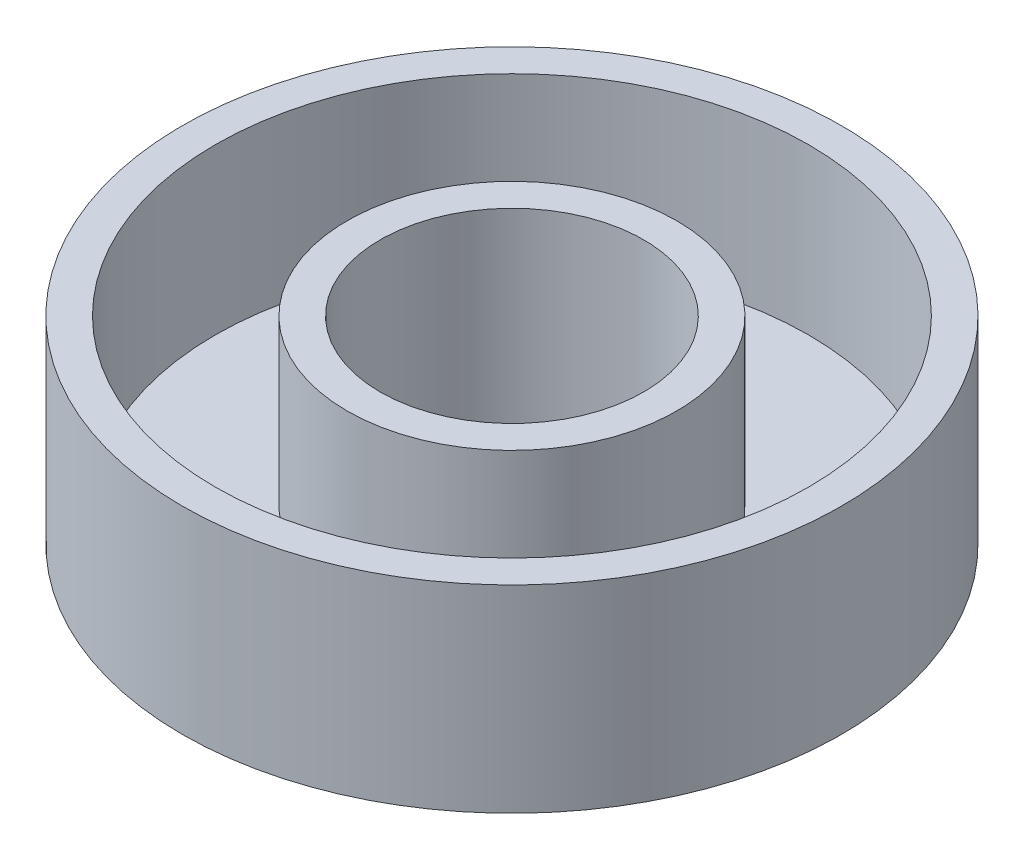
SolidWorks part; units mm, degrees
material "VITON"
ref_plane "Front Plane" through (0, 0, 0) normal (0, 0, 1) x (1, 0, 0)
ref_plane "Top Plane" through (0, 0, 0) normal (0, 1, 0) x (1, 0, 0)
ref_plane "Right Plane" through (0, 0, 0) normal (1, 0, 0) x (0, 0, -1)
sketch "Sketch1" plane through (0, 0, 0) normal (0, 1, 0) x (1, 0, 0)
  circle A0 centre (0, 0) radius 10
  dimension "D1" = 20
extrude "main extrusion" add sketch "Sketch1" along normal blind 6 contours A0
sketch "Sketch2" plane through (0, 6, 0) normal (0, 1, 0) x (1, 0, 0)
  circle A0 centre (0, 0) radius 4
  dimension "D1" = 8
extrude "ID bore" cut sketch "Sketch2" against normal blind 20
sketch "Sketch3" plane through (0, 6, 0) normal (0, 1, 0) x (1, 0, 0)
  circle A0 centre (0, 0) radius 9
  circle A1 centre (0, 0) radius 5
  dimension "D1" = 10
  dimension "D2" = 18
extrude "seal recess" cut sketch "Sketch3" against normal blind 5
equation "\"D1@Sketch1\" = \"small seal OD\""
equation "\"D1@main extrusion\" = \"small seal depth\""
equation "\"D1@Sketch2\"= \"small seal ID\""
equation "\"motor mount pattern diameter\"= 30mm"
equation "\"D2@Sketch3\" = \"small seal OD\" - 2mm"
equation "\"D1@Sketch3\" = \"small seal ID\" + 2mm"
equation "\"D1@seal recess\" = \"small seal depth\" - 1mm"
equation "\"bearing OD\" = 30mm"
equation "\"bearing outer race thickness\"= 1mm"
equation "\"bearing ID\"= 10mm"
equation "\"bearing depth\"= 9mm"
equation "\"bearing inner race thickness\"= 1mm"
equation "\"small seal OD\" = 20mm"
equation "\"small seal ID\"= 8mm"
equation "\"small seal depth\" = 6mm"
equation "\"big seal OD\" = 30mm"
